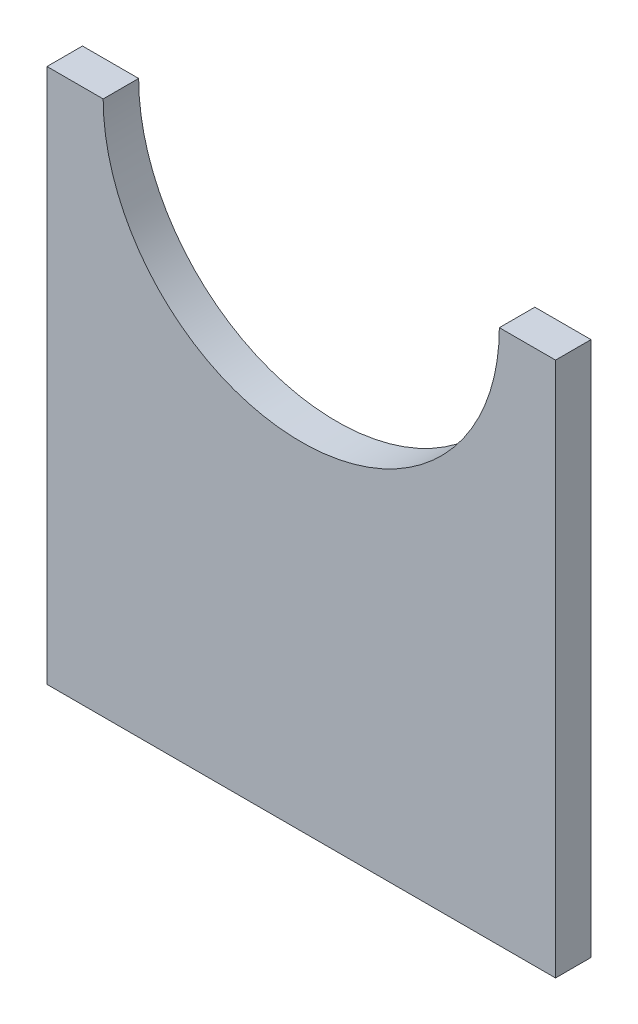
SolidWorks part; units mm, degrees
ref_plane "Front Plane" through (0, 0, 0) normal (0, 0, 1) x (1, 0, 0)
ref_plane "Top Plane" through (0, 0, 0) normal (0, 1, 0) x (1, 0, 0)
ref_plane "Right Plane" through (0, 0, 0) normal (1, 0, 0) x (0, 0, -1)
sketch "Sketch1" plane through (0, 0, 0) normal (0, 0, 1) x (1, 0, 0)
  line L4 (-16.75, 0) -> (-21.5, 0)
  line L6 (-21.5, -45.25) -> (-5, -45.25)
  line L7 (5, -45.25) -> (21.5, -45.25)
  line L8 (-21.5, 0) -> (-21.5, -45.25)
  line L9 (16.75, 0) -> (21.5, 0)
  line L10 (21.5, 0) -> (21.5, -45.25)
  line L12 (-5, -45.25) -> (5, -45.25)
  arc A0 (-16.75, 0) -> (16.75, 0) centre (0, 0) ccw
  point P5 (0, -16.75)
  dimension "D1" = 33.5
  dimension "D3" = 28.5
  dimension "D2" = 43
  dimension "D4" = 10
  dimension "D5" = 16.5
  dimension "D7" = 21.5
extrude "Boss-Extrude1" add sketch "Sketch1" along normal blind 3
